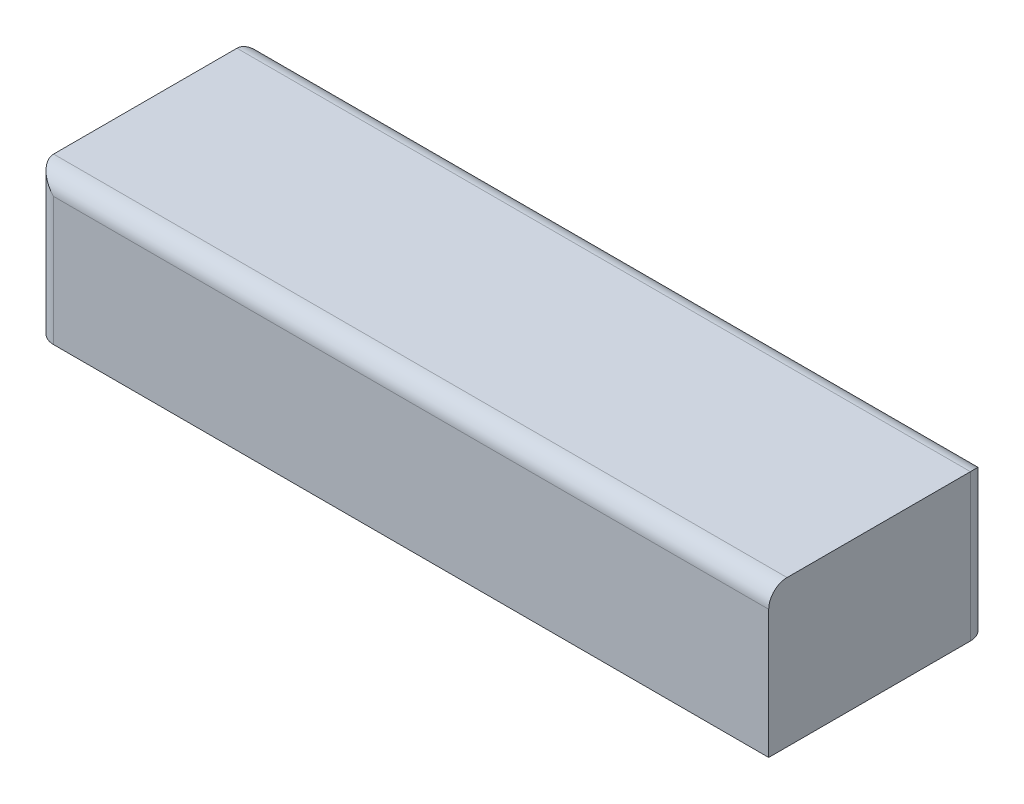
SolidWorks part; units mm, degrees
ref_plane "Front Plane" through (0, 0, 0) normal (0, 0, 1) x (1, 0, 0)
ref_plane "Top Plane" through (0, 0, 0) normal (0, 1, 0) x (1, 0, 0)
ref_plane "Right Plane" through (0, 0, 0) normal (1, 0, 0) x (0, 0, -1)
sketch "Sketch2" plane through (0, 0, 0) normal (0, 1, 0) x (1, 0, 0)
  line L1 (0, 0) -> (40, 0)
  line L2 (0, 0) -> (0, 12)
  line L3 (0, 12) -> (40, 12)
  line L4 (40, 0) -> (40, 12)
  dimension "D1" = 12
  dimension "D2" = 40
extrude "Boss-Extrude2" add sketch "Sketch2" along normal blind 8
fillet "Fillet1" radius 1 5 edges at (0, 4, -12) (40, 4, -12) (20, 8, -12) (0, 4, 0) (20, 8, 0)
